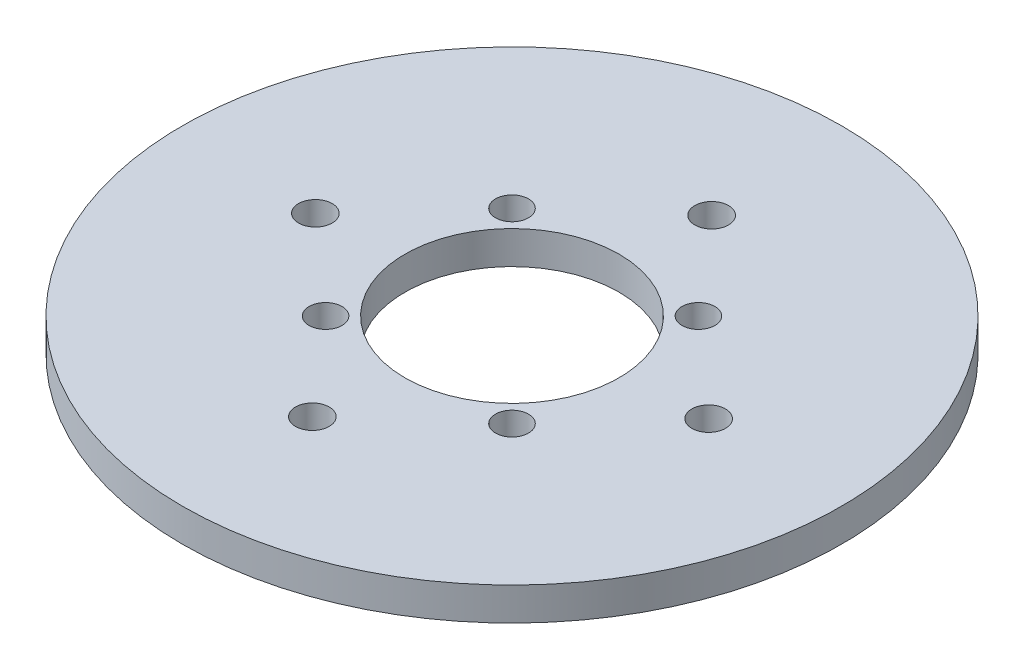
SolidWorks part; units mm, degrees
ref_plane "Front Plane" through (0, 0, 0) normal (0, 0, 1) x (1, 0, 0)
ref_plane "Top Plane" through (0, 0, 0) normal (0, 1, 0) x (1, 0, 0)
ref_plane "Right Plane" through (0, 0, 0) normal (1, 0, 0) x (0, 0, -1)
sketch "Sketch1" plane through (0, 0, 0) normal (0, 1, 0) x (1, 0, 0)
  circle A0 centre (0, 0) radius 63.5
  dimension "D1" = 127
extrude "Boss-Extrude1" add sketch "Sketch1" along normal blind 6.35
sketch "Sketch2" plane through (0, 6.35, 0) normal (0, 1, 0) x (1, 0, 0)
  circle A0 centre (0, 0) radius 20.6375
  dimension "D1" = 41.275
extrude "Cut-Extrude1" cut sketch "Sketch2" against normal through all
sketch "Sketch3" plane through (0, 6.35, 0) normal (0, 1, 0) x (1, 0, 0)
  line L0 (17.9605, 17.9605) -> (17.9605, -17.9605) construction
  line L1 (17.9605, -17.9605) -> (-17.9605, -17.9605) construction
  circle A0 centre (-17.9605, 17.9605) radius 3.175
  circle A1 centre (17.9605, 17.9605) radius 3.175
  circle A2 centre (17.9605, -17.9605) radius 3.175
  circle A3 centre (-17.9605, -17.9605) radius 3.175
  circle A4 centre (0, 0) radius 25.4 construction
  dimension "D1" = 50.8
  dimension "D2" = 6.35
extrude "Cut-Extrude2" cut sketch "Sketch3" against normal through all
sketch "Sketch4" plane through (0, 6.35, 0) normal (0, 1, 0) x (1, 0, 0)
  line L0 (-36.0793, -1.8126) -> (2.4299, 36.043) construction
  line L1 (-36.0793, -1.8126) -> (-2.4299, -36.043) construction
  line L2 (-2.4299, -36.043) -> (36.0793, 1.8126) construction
  line L3 (36.0793, 1.8126) -> (2.4299, 36.043) construction
  line L4 (-16.8247, 17.1152) -> (16.8247, -17.1152) construction
  line L5 (-19.2546, -18.9278) -> (19.2546, 18.9278) construction
  circle A0 centre (-36.0793, -1.8126) radius 3.25
  circle A1 centre (2.4299, 36.043) radius 3.25
  circle A2 centre (36.0793, 1.8126) radius 3.25
  circle A3 centre (-2.4299, -36.043) radius 3.25
  dimension "D1" = 6.5
  dimension "D2" = 54
  dimension "D3" = 48
extrude "Cut-Extrude3" cut sketch "Sketch4" against normal through all
